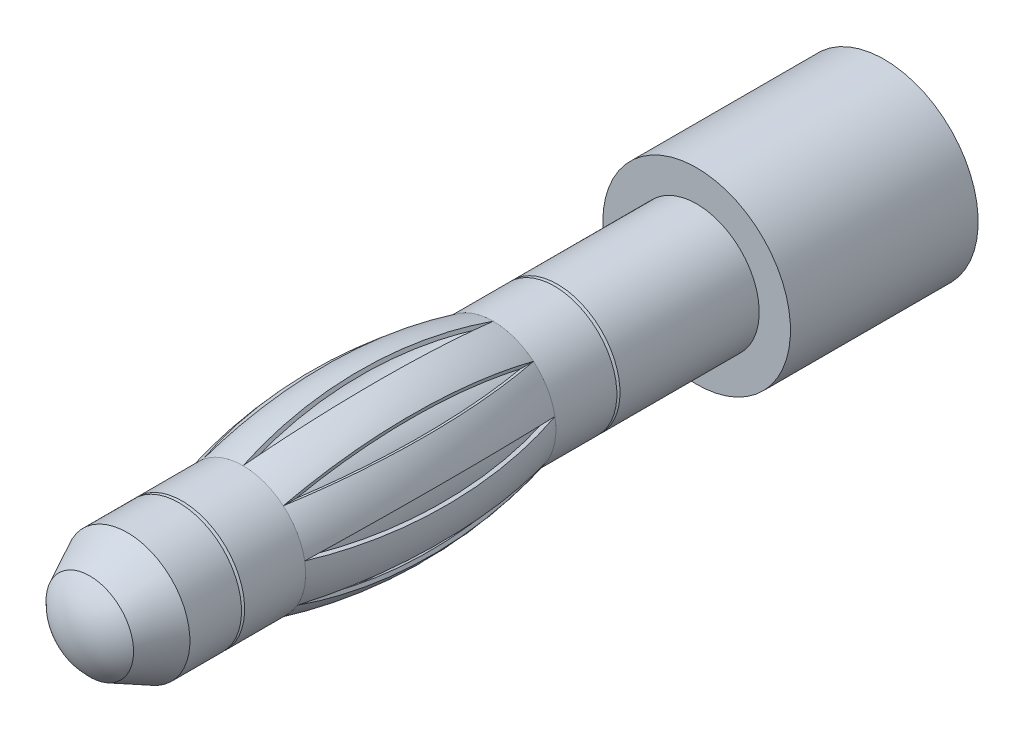
SolidWorks part; units mm, degrees
ref_plane "Plan de face" through (0, 0, 0) normal (0, 0, 1) x (1, 0, 0)
ref_plane "Plan de dessus" through (0, 0, 0) normal (0, 1, 0) x (1, 0, 0)
ref_plane "Plan de droite" through (0, 0, 0) normal (1, 0, 0) x (0, 0, -1)
sketch "Esquisse1" plane through (0, 0, 0) normal (1, 0, 0) x (0, 0, -1)
  line L0 (0, 0) -> (-22.0751, 0) construction
  line L1 (0, 1.55) -> (0, 3)
  line L2 (0, 3) -> (-6, 3)
  line L3 (-6, 3) -> (-6, 2)
  line L4 (-6, 2) -> (-10.45, 2)
  line L5 (-20.5, 2) -> (-22.45, 2)
  line L6 (-24.2, 2) -> (-25.4, 1.4)
  line L7 (-0.3, 1.25) -> (-6.7, 1.25)
  line L8 (-7, 0.95) -> (-7, 0)
  line L9 (-7, 0) -> (-26, 0)
  line L10 (-6.7, 1.25) -> (-7, 0.95)
  line L11 (0, 1.55) -> (-0.3, 1.25)
  line L13 (-12.9279, 2) -> (-12.9279, 1.9)
  line L14 (-12.9279, 1.9) -> (-20.0721, 1.9)
  line L15 (-20.0721, 1.9) -> (-20.0721, 2)
  line L16 (-16.5, 2.5) -> (-16.5, 0) construction
  line L17 (-22.55, 2) -> (-22.5, 1.9)
  line L18 (-22.5, 1.9) -> (-22.45, 2)
  line L19 (-22.5, 1.9) -> (-22.5, 2) construction
  line L21 (-10.5, 1.9) -> (-10.55, 2)
  line L22 (-10.45, 2) -> (-10.5, 1.9)
  line L23 (-10.55, 2) -> (-12.5, 2)
  line L25 (-22.55, 2) -> (-24.2, 2)
  arc A0 (-12.5, 2) -> (-20.5, 2) centre (-16.5, -13.75) ccw
  arc A2 (-25.4, 1.4) -> (-26, 0) centre (-24.0667, 0) ccw
  arc A3 (-20.0721, 2) -> (-12.9279, 2) centre (-16.5, -13.75) cw
  point P3 (0, 1.25)
  point P14 (-8.8964, -1.1669)
  point P16 (-16.5, 2.5)
  point P17 (-7, 1.25)
  dimension "D1" = 2.5
  dimension "D13" = 0.1
  dimension "D2" = 6
  dimension "D3" = 4
  dimension "D4" = 7
  dimension "D5" = 8
  dimension "D6" = 6
  dimension "D7" = 5
  dimension "D8" = 5.5
  dimension "D9" = 1.8
  dimension "D10" = 2.8
  dimension "D11" = 26
  dimension "D12" = 0.6
  dimension "D14" = 0.1
  dimension "D15" = 12
  dimension "D18" = 0.1
  dimension "D19" = 0.1
revolve "base" add sketch "Esquisse1" angle 360 about L0
sketch "Esquisse2" plane through (0, 0, 0) normal (0, 0, 1) x (1, 0, 0)
  line L0 (0, 0) -> (0, 3) construction
  line L1 (0.3, 2.5) -> (-0.3, 2.5)
  line L2 (-0.3, 2.5) -> (0, 2)
  line L3 (0.3, 2.5) -> (0, 2)
  line L4 (1.8368, 1.7223) -> (1.2856, 1.5321)
  line L5 (1.3772, 2.1079) -> (1.2856, 1.5321)
  line L6 (1.8368, 1.7223) -> (1.3772, 2.1079)
  line L7 (2.5141, 0.1387) -> (1.9696, 0.3473)
  line L8 (2.4099, 0.7296) -> (1.9696, 0.3473)
  line L9 (2.5141, 0.1387) -> (2.4099, 0.7296)
  line L10 (2.0151, -1.5098) -> (1.7321, -1)
  line L11 (2.3151, -0.9902) -> (1.7321, -1)
  line L12 (2.0151, -1.5098) -> (2.3151, -0.9902)
  line L13 (0.5731, -2.4518) -> (0.684, -1.8794)
  line L14 (1.137, -2.2466) -> (0.684, -1.8794)
  line L15 (0.5731, -2.4518) -> (1.137, -2.2466)
  line L16 (-1.137, -2.2466) -> (-0.684, -1.8794)
  line L17 (-0.5731, -2.4518) -> (-0.684, -1.8794)
  line L18 (-1.137, -2.2466) -> (-0.5731, -2.4518)
  line L19 (-2.3151, -0.9902) -> (-1.7321, -1)
  line L20 (-2.0151, -1.5098) -> (-1.7321, -1)
  line L21 (-2.3151, -0.9902) -> (-2.0151, -1.5098)
  line L22 (-2.4099, 0.7296) -> (-1.9696, 0.3473)
  line L23 (-2.5141, 0.1387) -> (-1.9696, 0.3473)
  line L24 (-2.4099, 0.7296) -> (-2.5141, 0.1387)
  line L25 (-1.3772, 2.1079) -> (-1.2856, 1.5321)
  line L26 (-1.8368, 1.7223) -> (-1.2856, 1.5321)
  line L27 (-1.3772, 2.1079) -> (-1.8368, 1.7223)
  circle A0 centre (0, 0) radius 3 construction
  circle A3 centre (0, 0) radius 2.5 construction
  circle A4 centre (0, 0) radius 2 construction
  circle A5 centre (0, 0) radius 2 construction
  point P6 (0.9442, 1.0337)
  point P8 (0, 2.5)
  point P12 (0, 1.364)
  point P13 (0, 0)
  point P14 (0, 2.5)
  point P15 (0, 0)
  point P40 (0, 0)
  point P41 (0, 0)
  point P42 (0, 1.3333)
  point P43 (0, 0)
  point P45 (0, 2)
  point P50 (1.2953, 1.5087)
  point P51 (-1.2089, 1.5933)
  point P52 (0.6847, -1.8791)
  dimension "D1" = 0.6
  dimension "D2" = 9
extrude "Enlèv. mat.-Extru.2" cut sketch "Esquisse2" along normal through all from offset 6
